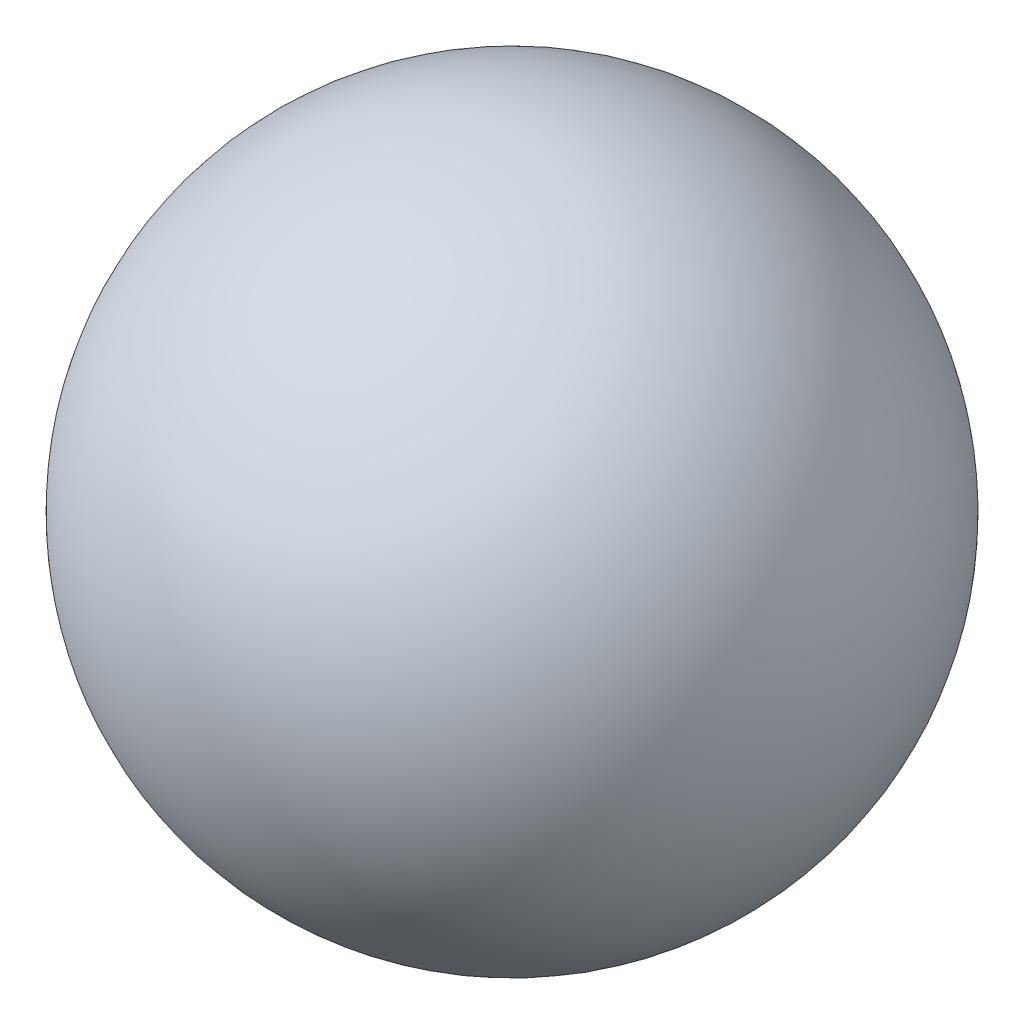
SolidWorks part; units mm, degrees
ref_plane "Front Plane" through (0, 0, 0) normal (0, 0, 1) x (1, 0, 0)
ref_plane "Top Plane" through (0, 0, 0) normal (0, 1, 0) x (1, 0, 0)
ref_plane "Right Plane" through (0, 0, 0) normal (1, 0, 0) x (0, 0, -1)
ref_plane "Plane1" through (0, 0, 0) normal (0, 0, -1) x (-1, 0, 0)
sketch "Sketch1" plane through (0, 0, 0) normal (0, 0, -1) x (-1, 0, 0)
  line L0 (-2.7799, 1.605) -> (-4.0941, 2.3638)
  line L1 (-2.6157, 1.5101) -> (-4.1704, 2.4078) construction
  arc A0 (-4.0941, 2.3638) -> (-2.7799, 1.605) centre (-3.437, 1.9844) ccw
revolve "Revolve1" add sketch "Sketch1" angle 360 about L1
